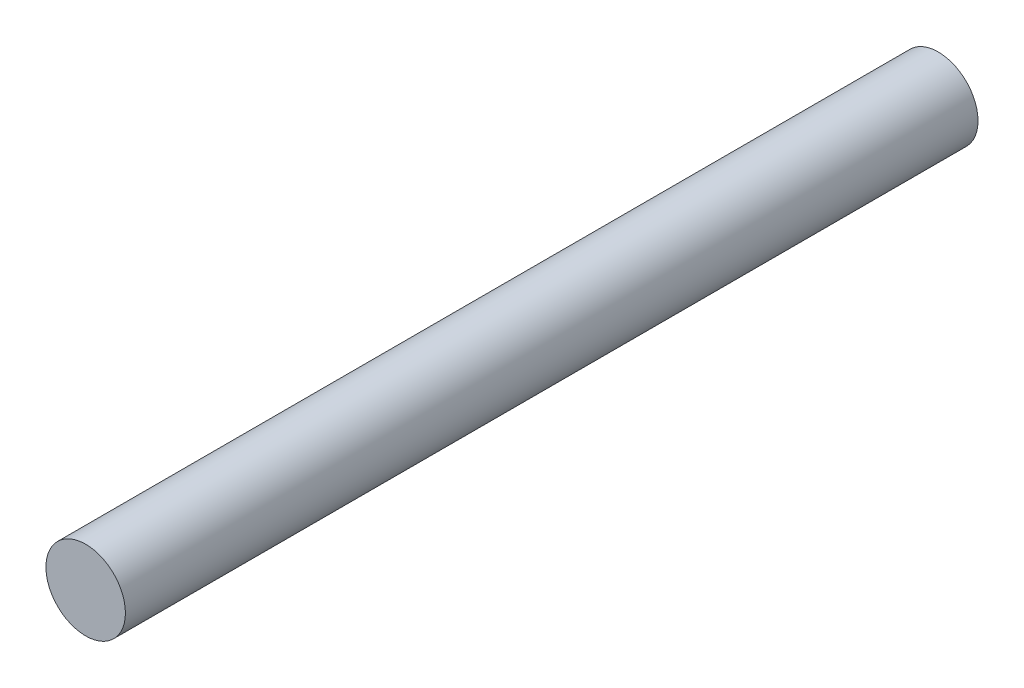
SolidWorks part; units mm, degrees
ref_plane "Front Plane" through (0, 0, 0) normal (0, 0, 1) x (1, 0, 0)
ref_plane "Top Plane" through (0, 0, 0) normal (0, 1, 0) x (1, 0, 0)
ref_plane "Right Plane" through (0, 0, 0) normal (1, 0, 0) x (0, 0, -1)
sketch "outerd" plane through (0, 0, 0) normal (0, 0, 1) x (1, 0, 0)
  circle A0 centre (0, 0) radius 84.5
  dimension "D1" = 169
extrude "bodytube" add sketch "outerd" against normal blind 1812.8
sketch "mid-centerline" plane through (0, 0, 0) normal (0, 1, 0) x (1, 0, 0)
  line L0 (0, 0) -> (0, 1812.8) construction
  line L1 (-84.5, 0) -> (84.5, 0) construction
  line L2 (84.5, 1812.8) -> (-84.5, 1812.8) construction
